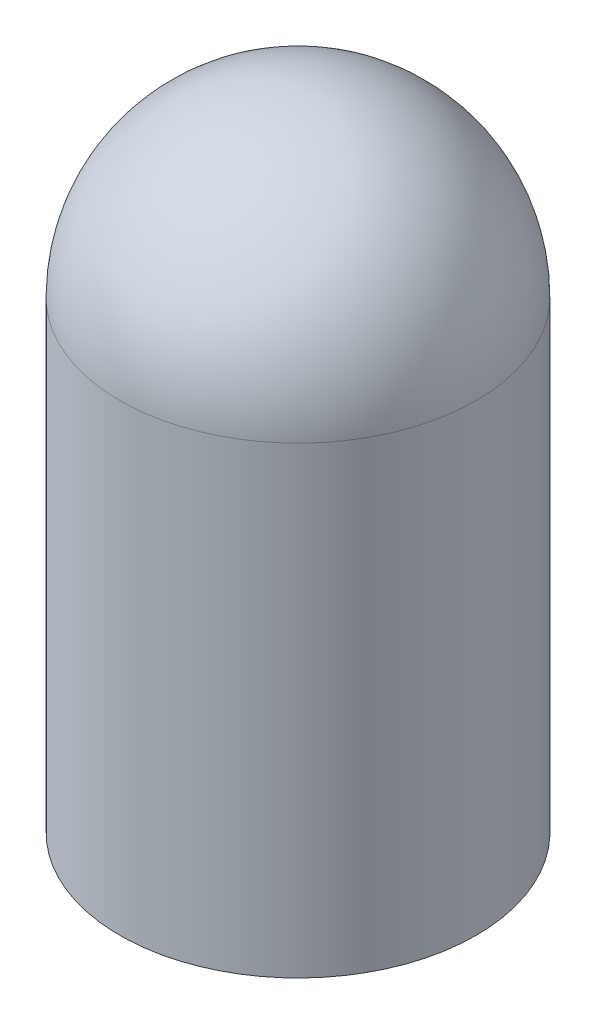
SolidWorks part; units mm, degrees
ref_plane "Спереди" through (0, 0, 0) normal (0, 0, 1) x (1, 0, 0)
ref_plane "Сверху" through (0, 0, 0) normal (0, 1, 0) x (1, 0, 0)
ref_plane "Справа" through (0, 0, 0) normal (1, 0, 0) x (0, 0, -1)
sketch "Эскиз1" plane through (0, 0, 0) normal (0, 0, 1) x (1, 0, 0)
  line L0 (0, 9) -> (0, 6.5)
  line L1 (0, 0) -> (2.5, 0)
  line L2 (0, 0) -> (0, 6.5)
  line L3 (0, 6.5) -> (2.5, 6.5)
  line L4 (2.5, 0) -> (2.5, 6.5)
  arc A1 (2.5, 6.5) -> (0, 9) centre (0, 6.5) ccw
  dimension "D1" = 2.5
  dimension "D2" = 9
revolve "Повернуть1" add sketch "Эскиз1" angle 360 about L2
